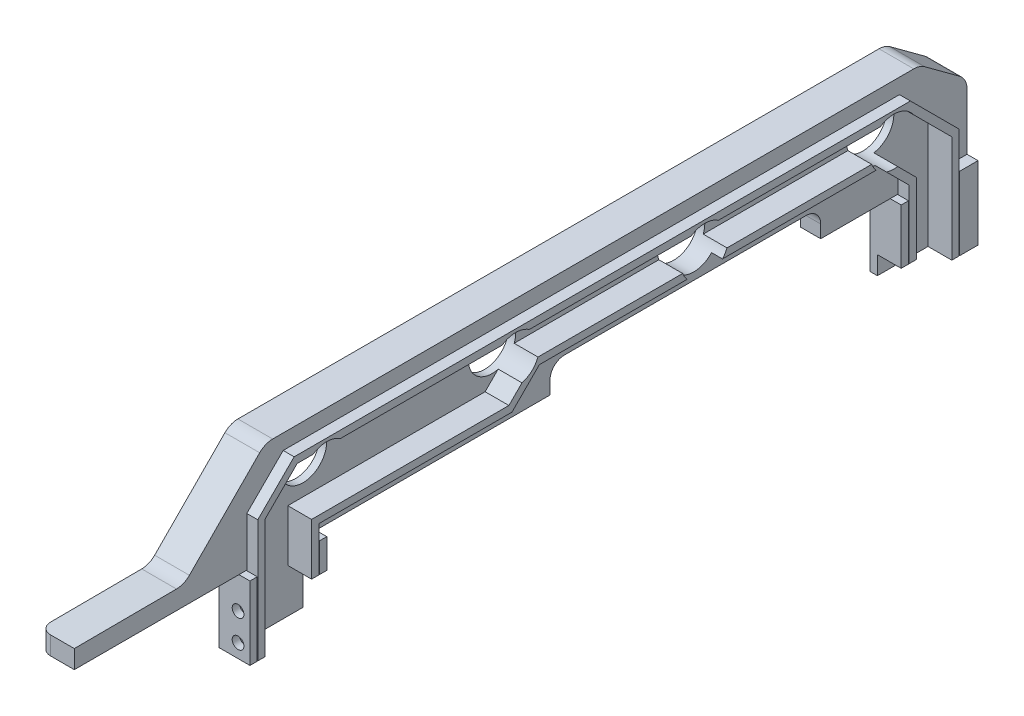
SolidWorks part; units mm, degrees
ref_plane "Front Plane" through (0, 0, 0) normal (0, 0, 1) x (1, 0, 0)
ref_plane "Top Plane" through (0, 0, 0) normal (0, 1, 0) x (1, 0, 0)
ref_plane "Right Plane" through (0, 0, 0) normal (1, 0, 0) x (0, 0, -1)
sketch "Sketch1" plane through (0, 0, 0) normal (1, 0, 0) x (0, 0, -1)
  line L0 (0, 0) -> (-130, 0)
  line L1 (0, 0) -> (74, 0) construction
  line L2 (0, 0) -> (0, 7.5)
  line L3 (0, 7.5) -> (74, 7.5)
  line L4 (74, 7.5) -> (74, 0)
  line L5 (74, 0) -> (114, 0)
  line L6 (-130, 0) -> (-130, 5)
  line L7 (-130, 5) -> (-100.0004, 5.1483)
  line L8 (-100.0004, 5.1483) -> (-77.8685, 27.5)
  line L9 (114, 0) -> (114, 18)
  line L10 (114, 18) -> (101.0882, 27.5)
  line L11 (101.0882, 27.5) -> (-77.8685, 27.5)
  dimension "D1" = 130
  dimension "D2" = 74
  dimension "D3" = 7.5
  dimension "D4" = 40
  dimension "D5" = 30
  dimension "D6" = 5
  dimension "D7" = 135
  dimension "D8" = 20
  dimension "D9" = 18
extrude "Boss-Extrude1" add sketch "Sketch1" along normal blind 25
sketch "Sketch4" plane through (25, 0, 0) normal (1, 0, 0) x (0, 0, -1)
  line L11 (-130, 0) -> (0, 0) construction
  line L12 (-130, 0) -> (0, 0) construction
  line L13 (-100.8762, 0) -> (0, 0)
  line L14 (0, 0) -> (111, 0)
  line L15 (74, 0) -> (114, 0) construction
  line L16 (111, 0) -> (111, 3)
  line L22 (-3, 3) -> (-3, 10.5)
  line L23 (-3, 10.5) -> (77, 10.5)
  line L24 (77, 10.5) -> (77, 3)
  line L25 (77, 3) -> (111, 3)
  line L26 (111, 3) -> (111, 16.4828)
  line L27 (111, 16.4828) -> (100.1035, 24.5)
  line L28 (100.1035, 24.5) -> (-76.6172, 24.5)
  line L29 (-76.6172, 24.5) -> (-97.9057, 3)
  line L30 (-97.9057, 3) -> (-3, 3)
  line L35 (111, 3) -> (111, 16.4828)
  line L36 (111, 16.4828) -> (100.1035, 24.5)
  line L37 (100.1035, 24.5) -> (-76.6172, 24.5)
  line L38 (-76.6172, 24.5) -> (-100.8762, 0)
  dimension "D1" = 3
extrude "Cut-Extrude1" cut sketch "Sketch4" against normal blind 4
ref_plane "Plane1" through (12.5, 0, 0) normal (1, 0, 0) x (0, 0, -1)
mirror "Mirror2" about plane through (12.5, 0, 0) normal (1, 0, 0) of "Cut-Extrude1"
fillet "Fillet1" radius 4 2 edges at (12.5, 7.5, -74) (12.5, 7.5, 0)
fillet "Fillet2" radius 10 8 edges at (23, 16.4828, -111) (23, 24.5, -100.1035) (2, 16.4828, -111) (2, 24.5, -100.1035) (2, 24.5, 76.6172) (23, 24.5, 76.6172) (2, 0, 100.8762) (23, 0, 100.8762)
fillet "Fillet3" radius 5 4 edges at (12.5, 18, -114) (12.5, 27.5, -101.0882) (12.5, 27.5, 77.8685) (12.5, 5.1483, 100.0004)
fillet "Fillet4" radius 3 2 edges at (0, 2.5, 130) (25, 2.5, 130)
sketch "Sketch5" plane through (12.5, 0, 0) normal (1, 0, 0) x (0, 0, -1)
  line L0 (-117.866, 5.06) -> (-103.7939, 19.2718)
  line L1 (-102.0714, 5.138) -> (-127, 5.0148) construction
  line L2 (-79.3359, 26.018) -> (-98.5432, 6.62) construction
  line L3 (-103.7939, 19.2718) -> (-72.6053, 19.2718)
  line L4 (-117.866, 5.06) -> (-95.866, 5.06)
  line L5 (-79.552, 21.536) -> (-97.9414, 2.964) construction
  line L6 (-72.6053, 19.2718) -> (-95.866, 5.06)
  dimension "D1" = 22
  dimension "D2" = 20
extrude "Boss-Extrude2" add sketch "Sketch5" along normal blind 3 and the other way blind 3
fillet "Fillet5" radius 3 1 edges at (12.5, 19.2718, 103.7939)
sketch "Sketch6" plane through (0, 0, 0) normal (0, -1, 0) x (1, 0, 0)
  line L1 (0, -111) -> (0, -114) construction
  line L2 (0, -111) -> (4, -111)
  line L3 (0, -111) -> (0, -114)
  line L4 (0, -114) -> (25, -114)
  line L5 (25, -111) -> (25, -114)
  line L6 (0, -111) -> (25, -114) construction
  line L7 (0, -114) -> (25, -111) construction
  line L8 (4, -111) -> (0, -111) construction
  line L9 (25, -114) -> (0, -114) construction
  line L10 (4, -74) -> (4, -111) construction
  line L11 (4, -111) -> (21, -111) construction
  line L12 (4, -111) -> (4, -93)
  line L13 (4, -93) -> (21, -93)
  line L14 (21, -111) -> (21, -93)
  line L15 (4, -111) -> (21, -93) construction
  line L16 (4, -93) -> (21, -111) construction
  line L17 (21, -74) -> (21, -111) construction
  line L18 (4, -111) -> (21, -111) construction
  line L19 (21, -111) -> (25, -111)
  line L21 (19, -95) -> (6, -95)
  line L22 (19, -95) -> (19, -109)
  line L23 (19, -109) -> (6, -109)
  line L24 (6, -95) -> (6, -109)
  line L25 (19, -95) -> (6, -109) construction
  line L26 (19, -109) -> (6, -95) construction
  point P6 (12.5, -112.5)
  point P16 (12.5, -102)
  point P21 (12.5, -102)
  dimension "D1" = 18
  dimension "D2" = 2
  dimension "D3" = 2
extrude "Boss-Extrude3" add sketch "Sketch6" along normal blind 20
sketch "Sketch7" plane through (0, -20, 0) normal (0, -1, 0) x (1, 0, 0)
  line L0 (19, -109) -> (19, -95) construction
  line L1 (19, -95) -> (6, -95)
  line L2 (19, -95) -> (19, -93)
  line L3 (19, -93) -> (6, -93)
  line L4 (6, -95) -> (6, -93)
  line L5 (19, -95) -> (6, -93) construction
  line L6 (19, -93) -> (6, -95) construction
  line L7 (19, -95) -> (6, -95) construction
  line L8 (21, -93) -> (4, -93) construction
  line L9 (6, -95) -> (6, -109) construction
  point P4 (12.5, -94)
sketch "Sketch8" plane through (0, 0, 0) normal (0, -1, 0) x (1, 0, 0)
  line L5 (21, 85) -> (21, 130) construction
  line L6 (21, 105.0473) -> (21, 0) construction
  line L8 (22, 130) -> (3, 130) construction
  line L9 (4, 105.0473) -> (4, 0) construction
  line L10 (21, 85) -> (4, 85)
  line L11 (21, 85) -> (21, 64)
  line L12 (21, 64) -> (19, 64)
  line L13 (4, 85) -> (4, 64)
  line L14 (21, 85) -> (4, 64) construction
  line L15 (21, 64) -> (4, 85) construction
  line L16 (19, 64) -> (6, 64) construction
  line L17 (6, 64) -> (19, 64) construction
  line L18 (6, 64) -> (6, 83)
  line L19 (6, 83) -> (19, 83)
  line L20 (19, 64) -> (19, 83)
  line L21 (6, 64) -> (19, 83) construction
  line L22 (6, 83) -> (19, 64) construction
  line L23 (6, 64) -> (4, 64)
  point P9 (12.5, 74.5)
  point P16 (12.5, 73.5)
  dimension "D1" = 45
  dimension "D2" = 21
  dimension "D3" = 2
  dimension "D4" = 2
  dimension "D5" = 2
extrude "Boss-Extrude4" add sketch "Sketch8" along normal blind 20
sketch "Sketch9" plane through (0, 0, 0) normal (0, -1, 0) x (1, 0, 0)
  line L0 (6, 64) -> (6, 83) construction
  line L1 (6, 64) -> (19, 64)
  line L2 (6, 64) -> (6, 66)
  line L3 (6, 66) -> (19, 66)
  line L4 (19, 64) -> (19, 66)
  line L5 (6, 64) -> (19, 66) construction
  line L6 (6, 66) -> (19, 64) construction
  line L7 (19, 83) -> (19, 64) construction
  point P4 (12.5, 65)
  dimension "D1" = 2
extrude "Boss-Extrude5" add sketch "Sketch9" along normal blind 8
extrude "Cut-Extrude2" cut sketch "Sketch7" against normal blind 5 contours L3 L4 L1 L2
sketch "Sketch11" plane through (0, 0, -114) normal (0, 0, -1) x (-1, 0, 0)
  line L0 (0, -20) -> (0, -12.5) construction
  line L1 (0, -20) -> (-25, -20) construction
  line L2 (0, -20) -> (0, 15.4713) construction
  line L3 (0, -16.25) -> (-25, -16.25) construction
  line L4 (-25, -20) -> (-25, 15.4713) construction
  line L5 (0, -16.25) -> (-9.25, -16.25) construction
  line L6 (-12.5, -20) -> (-12.5, -5) construction
  line L7 (0, -20) -> (0, -16.25)
  line L8 (-25, -20) -> (-25, -12.5) construction
  line L9 (-25, -12.5) -> (0, -12.5) construction
  circle A0 centre (-9.25, -16.25) radius 1.6
  circle A1 centre (-15.75, -16.25) radius 1.6
  circle A2 centre (-15.75, -8.75) radius 1.6
  circle A3 centre (-9.25, -8.75) radius 1.6
  circle A4 centre (-15.75, -16.25) radius 3 construction
  dimension "D2" = 3.2
  dimension "D5" = 6
  dimension "D1" = 9.25
  dimension "D3" = 3.75
  dimension "D4" = 7.5
extrude "Cut-Extrude3" cut sketch "Sketch11" against normal up to surface (19 mm away) contours A1 | A2 | A3 | A0 up to face at (12.5, -7.5, -95)
sketch "Sketch12" plane through (0, 0, 85) normal (0, 0, 1) x (1, 0, 0)
  line L0 (15.75, -8.75) -> (21, -8.75) construction
  line L1 (15.75, -8.75) -> (15.75, -5) construction
  line L3 (12.5, -20) -> (12.5, -5) construction
  line L6 (0, -12.5) -> (25, -12.5) construction
  line L7 (4, -20) -> (21, -20) construction
  line L8 (4, -20) -> (4, 0) construction
  line L9 (21, -20) -> (21, 0) construction
  circle A0 centre (15.75, -16.25) radius 1.6
  circle A1 centre (9.25, -16.25) radius 1.6
  circle A2 centre (9.25, -8.75) radius 1.6
  circle A3 centre (15.75, -8.75) radius 1.6
  circle A4 centre (9.25, -16.25) radius 3 construction
  dimension "D1" = 3.2
  dimension "D2" = 5.25
  dimension "D3" = 3.75
extrude "Cut-Extrude4" cut sketch "Sketch12" against normal up to surface (2 mm away) up to face at (12.5, -10, 83)
sketch "MAKE THIS A SQUARE OR SMTH" plane through (4, 0, 0) normal (-1, 0, 0) x (0, 0, 1)
  line L0 (-37, 7.5) -> (-37, 24.5) construction
  line L1 (-70, 7.5) -> (-4, 7.5) construction
  line L2 (-96.8211, 24.5) -> (72.4461, 24.5) construction
  line L3 (-37, 16) -> (-111, 16) construction
  line L4 (-37, 16) -> (84, 16) construction
  line L6 (-111, 16) -> (-13.5, 16) construction
  line L7 (-13.5, 16) -> (-13.5, 7.5) construction
  line L8 (-111, 16) -> (-91, 16) construction
  circle A1 centre (-91, 16) radius 6.5
  circle A2 centre (-39.3333, 16) radius 6.5
  circle A3 centre (64, 16) radius 6.5
  circle A4 centre (12.3333, 16) radius 6.5
  dimension "D5" = 13
  dimension "D1" = 74
  dimension "D2" = 121
  dimension "D3" = 97.5
  dimension "D4" = 20
  dimension "D6" = 51.6667
sketch "Sketch14" plane through (12.5, 0, 0) normal (1, 0, 0) x (0, 0, -1)
  line L0 (-83, 0) -> (-83, 13.4752)
  line L1 (-66, 0) -> (-66, 4)
  line L2 (-66, 4) -> (-13.3251, 4)
  line L3 (-13.3251, 4) -> (-5.8251, 11.5)
  line L4 (-5.8251, 11.5) -> (87.0794, 11.5)
  line L5 (95, 0) -> (95, 3.5794)
  line L6 (95, 3.5794) -> (87.0794, 11.5)
  line L7 (109, 0) -> (109, 10.0924)
  line L8 (109, -20) -> (109, 0) construction
  line L9 (95, 0) -> (109, 0) construction
  line L10 (109, 10.0924) -> (95.5924, 23.5)
  line L15 (-72.9752, 23.5) -> (-83, 13.4752)
  line L16 (-83, 0) -> (-66, 0)
  line L17 (95, 0) -> (109, 0)
  line L18 (95.5924, 23.5) -> (-72.9752, 23.5)
  line L19 (-64, 0) -> (0, 0) construction
  line L20 (99.447, 27.5) -> (-75.783, 27.5) construction
  line L21 (70, 7.5) -> (4, 7.5) construction
  dimension "D1" = 135
  dimension "D2" = 135
  dimension "D3" = 135
  dimension "D4" = 135
  dimension "D5" = 4
  dimension "D6" = 4
  dimension "D7" = 4
extrude "Cut-Extrude5" cut sketch "Sketch14" against normal blind 6.5 and the other way blind 6.5
sketch "Sketch17" plane through (0, 0, 130) normal (0, 0, 1) x (1, 0, 0)
  line L0 (12.5, -20) -> (25, -20)
  line L1 (21, -20) -> (4, -20) construction
  line L2 (25, -20) -> (25, 27.5)
  line L3 (25, 27.5) -> (9.5, 27.5)
  line L4 (0, 27.5) -> (25, 27.5) construction
  line L5 (9.5, 5.138) -> (9.5, 27.5)
  line L6 (12.5, -20) -> (12.5, 0)
  line L7 (22, 0) -> (3, 0) construction
  line L8 (12.5, 0) -> (9.5, 0)
  line L9 (21, 0) -> (4, 0) construction
  line L10 (9.5, 0) -> (9.5, 5.138)
extrude "Cut-Extrude7" cut sketch "Sketch17" against normal through all
sketch "Sketch18" plane through (6, 0, 0) normal (1, 0, 0) x (0, 0, -1)
  line L0 (-83, -20) -> (-82.85, -20)
  line L1 (-64, -20) -> (-83, -20) construction
  line L2 (-82.85, -20) -> (-80.85, -20)
  line L3 (-66, -8) -> (-66.15, -8)
  line L4 (-66.15, -8) -> (-68.15, -8)
  line L5 (-66.15, -8) -> (-66.15, 4.15)
  line L6 (-66.15, 4.15) -> (-13.3872, 4.15)
  line L7 (-13.3872, 4.15) -> (-5.8872, 11.65)
  line L8 (-5.8872, 11.65) -> (87.1415, 11.65)
  line L9 (87.1415, 11.65) -> (95.15, 3.6415)
  line L10 (95.15, 3.6415) -> (95.15, -15)
  line L11 (95, -15) -> (95, 3.5794) construction
  line L12 (95, -15) -> (95.15, -15)
  line L13 (95, 3.5794) -> (87.0794, 11.5) construction
  line L14 (-47.2142, 4) -> (-47.2142, 4.15) construction
  line L15 (-13.3251, 4) -> (-66, 4) construction
  line L16 (-10.7524, 6.7848) -> (-10.6464, 6.6787) construction
  line L17 (-68.15, -10) -> (-68.15, 6.15) construction
  line L18 (-5.8251, 11.5) -> (-13.3251, 4) construction
  line L19 (91.2889, 7.2905) -> (91.3949, 7.3966) construction
  line L20 (61.1672, 11.5) -> (61.1672, 11.65) construction
  line L21 (-5.8251, 11.5) -> (87.0794, 11.5) construction
  line L22 (95.15, -15) -> (97.15, -15)
  line L23 (-68.15, -8) -> (-68.15, 6.15)
  line L24 (-68.15, 6.15) -> (-14.2157, 6.15)
  line L25 (-14.2157, 6.15) -> (-6.7157, 13.65)
  line L26 (-6.7157, 13.65) -> (87.97, 13.65)
  line L27 (87.97, 13.65) -> (97.15, 4.47)
  line L28 (97.15, 4.47) -> (97.15, -15)
  line L29 (-82.85, -20) -> (-82.85, 13.413)
  line L30 (-49.2142, 4) -> (-49.2142, 4.15) construction
  line L31 (-9.3382, 8.199) -> (-9.2321, 8.093) construction
  line L32 (89.8746, 8.7048) -> (89.9807, 8.8108) construction
  line L33 (59.1672, 11.5) -> (59.1672, 11.65) construction
  line L34 (-66, -10) -> (-68.15, -10) construction
  line L35 (97.15, 4.47) -> (97.15, -17) construction
  line L36 (95, -17) -> (97.15, -17) construction
  line L37 (-82.85, 13.413) -> (-72.913, 23.35)
  line L38 (-72.9752, 23.5) -> (-83, 13.4752) construction
  line L39 (-72.913, 23.35) -> (95.5303, 23.35)
  line L40 (-78.8315, 17.4315) -> (-78.9376, 17.5376) construction
  line L41 (-83, -20) -> (-83, 13.4752)
  line L42 (-68.3764, 23.35) -> (-68.3764, 23.5) construction
  line L43 (-72.9752, 23.5) -> (95.5924, 23.5) construction
  line L44 (95.5303, 23.35) -> (108.85, 10.0303)
  line L45 (108.85, 10.0303) -> (108.85, -20)
  line L46 (93, -20) -> (109, -20) construction
  line L47 (109, 10.0924) -> (95.5924, 23.5) construction
  line L48 (101.5774, 17.3029) -> (101.6835, 17.4089) construction
  line L49 (108.85, -12.75) -> (109, -12.75) construction
  line L50 (109, 0) -> (109, -20) construction
  line L51 (-80.85, -20) -> (-80.85, 12.5846)
  line L52 (-80.85, 12.5846) -> (-72.0846, 21.35)
  line L53 (-72.0846, 21.35) -> (94.7019, 21.35)
  line L54 (94.7019, 21.35) -> (106.85, 9.2019)
  line L55 (106.85, 9.2019) -> (106.85, -20)
  line L56 (-82.85, -20) -> (-80.85, -20)
  line L57 (106.85, -20) -> (108.85, -20)
  line L58 (-83, 13.4752) -> (-72.9752, 23.5) construction
  line L59 (-83, 13.4752) -> (-72.9752, 23.5)
  line L60 (-72.9752, 23.5) -> (95.5924, 23.5)
  line L61 (95.5924, 23.5) -> (109, 10.0924)
  line L62 (109, 10.0924) -> (109, -20)
  line L63 (109, -20) -> (108.85, -20)
  line L64 (-66, -8) -> (-66, 4)
  line L65 (-66, 4) -> (-13.3251, 4)
  line L66 (-13.3251, 4) -> (-5.8251, 11.5)
  line L67 (-5.8251, 11.5) -> (87.0794, 11.5)
  line L68 (87.0794, 11.5) -> (95, 3.5794)
  line L69 (95, 3.5794) -> (95, -15)
  line L70 (-66.1464, -8) -> (-66, -8)
  dimension "D1" = 0.15
  dimension "D3" = 2
extrude "Boss-Extrude6" add sketch "Sketch18" along normal up to surface (6.5 mm away) contours L54 L55 L19 L45 L44 L39 L37 L29 L5 L51 L52 L53 L48 L6 up to face at (12.5, -10, 84)
sketch "Sketch24" plane through (6, 0, 0) normal (1, 0, 0) x (0, 0, -1)
  line L0 (-83, -20) -> (-82.85, -20)
  line L1 (-82.85, -20) -> (-82.85, 13.413)
  line L2 (-82.85, 13.413) -> (-72.913, 23.35)
  line L3 (-72.913, 23.35) -> (95.5303, 23.35)
  line L4 (95.5303, 23.35) -> (108.85, 10.0303)
  line L5 (108.85, 10.0303) -> (108.85, -20)
  line L6 (108.85, -20) -> (109, -20)
  line L7 (109, -20) -> (109, 10.0924)
  line L8 (109, 10.0924) -> (95.5924, 23.5)
  line L9 (95.5924, 23.5) -> (-72.9752, 23.5)
  line L10 (-72.9752, 23.5) -> (-83, 13.4752)
  line L11 (-83, 13.4752) -> (-83, -20)
  line L12 (-66.15, -8) -> (-66, -8)
  line L13 (-66, -8) -> (-66, 4)
  line L14 (-66, 4) -> (-13.3251, 4)
  line L15 (-13.3251, 4) -> (-5.8251, 11.5)
  line L16 (-5.8251, 11.5) -> (87.0794, 11.5)
  line L17 (87.0794, 11.5) -> (95, 3.5794)
  line L18 (95, 3.5794) -> (95, -15)
  line L19 (95, -15) -> (95.15, -15)
  line L20 (95.15, -15) -> (95.15, 3.6415)
  line L21 (95.15, 3.6415) -> (87.1415, 11.65)
  line L22 (87.1415, 11.65) -> (-5.8872, 11.65)
  line L23 (-5.8872, 11.65) -> (-13.3872, 4.15)
  line L24 (-13.3872, 4.15) -> (-66.15, 4.15)
  line L25 (-66.15, 4.15) -> (-66.15, -8)
extrude "Boss-Extrude8" add sketch "Sketch24" along normal up to surface (3.5 mm away) contours L1 L2 L3 L4 L5 L6 L7 L8 L9 L10 L11 L0 | L13 L14 L15 L16 L17 L18 L19 L20 L21 L22 L23 L24 L25 L12 up to face at (9.5, 12.7959, 4.6522)
extrude "Cut-Extrude8" cut sketch "MAKE THIS A SQUARE OR SMTH" against normal through all
